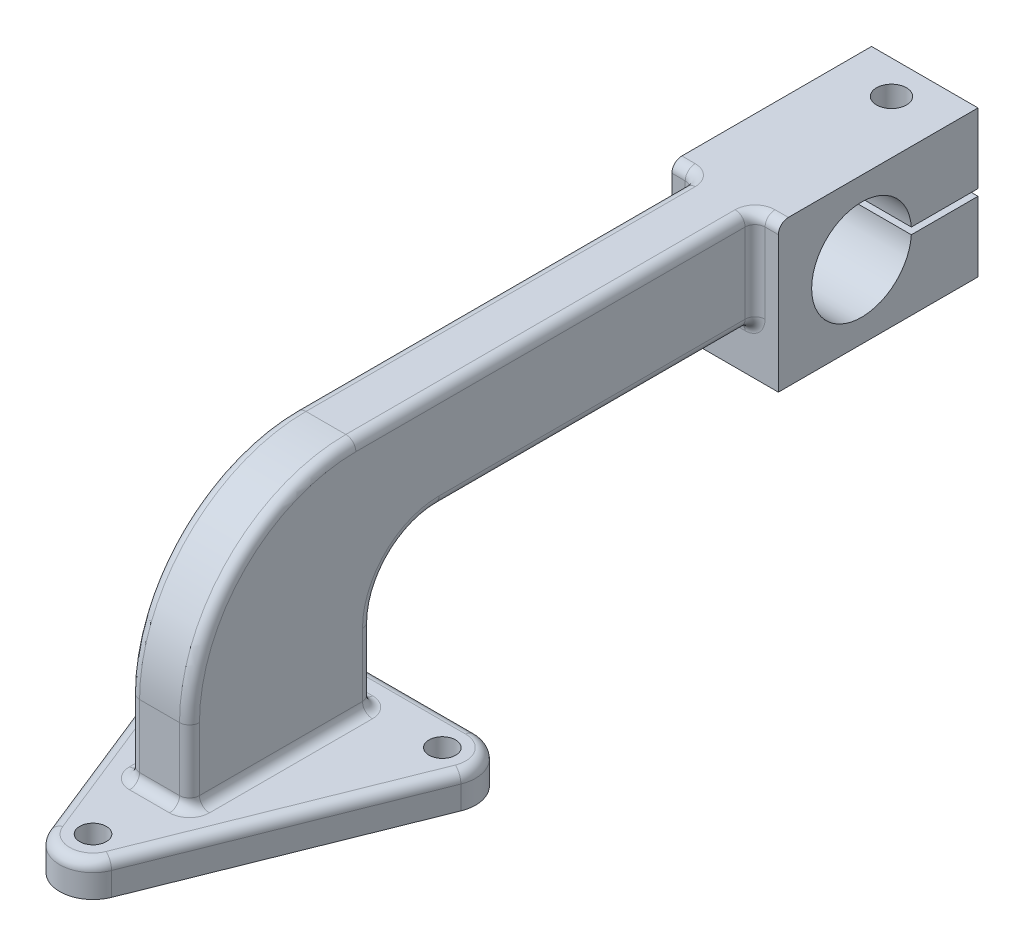
SolidWorks part; units mm, degrees
ref_plane "Front Plane" through (0, 0, 0) normal (0, 0, 1) x (1, 0, 0)
ref_plane "Top Plane" through (0, 0, 0) normal (0, 1, 0) x (1, 0, 0)
ref_plane "Right Plane" through (0, 0, 0) normal (1, 0, 0) x (0, 0, -1)
sketch "Sketch1" plane through (0, 0, 0) normal (1, 0, 0) x (0, 0, -1)
  line L0 (90.4912, -6.4386) -> (-4.5088, -6.4386)
  line L1 (-24.5088, -26.4386) -> (-24.5088, -48.4386)
  line L2 (-24.5088, -48.4386) -> (-79.5088, -48.4386)
  line L3 (-79.5088, -48.4386) -> (-79.5088, -37.4386)
  line L4 (-79.5088, -37.4386) -> (-79.5088, -26.4386)
  line L5 (-29.5088, 23.5614) -> (90.4912, 23.5614)
  line L6 (90.4912, 23.5614) -> (90.4912, -6.4386)
  arc A0 (-4.5088, -6.4386) -> (-24.5088, -26.4386) centre (-4.5088, -26.4386) ccw
  arc A1 (-79.5088, -26.4386) -> (-29.5088, 23.5614) centre (-29.5088, -26.4386) cw
  point P10 (0, 0)
  dimension "D4" = 20
  dimension "D5" = 50
  dimension "D1" = 22
  dimension "D2" = 22
  dimension "D3" = 55
  dimension "D6" = 95
  dimension "D7" = 30
extrude "Boss-Extrude1" add sketch "Sketch1" along normal mid plane 18
sketch "Sketch2" plane through (0, 0, -90.4912) normal (0, 0, -1) x (-1, 0, 0)
  line L0 (-16, 23.5614) -> (16, 23.5614)
  line L1 (16, 23.5614) -> (16, -20.4386)
  line L2 (16, -20.4386) -> (-16, -20.4386)
  line L3 (-16, -20.4386) -> (-16, 23.5614)
  line L4 (0, 23.5614) -> (0, -20.4386) construction
  line L5 (0, 23.5614) -> (0, -6.4386) construction
  line L6 (-9, 23.5614) -> (9, 23.5614) construction
  line L7 (-9, -6.4386) -> (9, -6.4386) construction
  line L8 (-16, 1.5614) -> (16, 1.5614) construction
  line L9 (-9, 8.5614) -> (9, 8.5614) construction
  line L10 (-9, -6.4386) -> (-9, 23.5614) construction
  line L11 (9, -6.4386) -> (9, 23.5614) construction
  point P20 (0, 0)
  dimension "D1" = 32
  dimension "D2" = 44
extrude "Boss-Extrude2" add sketch "Sketch2" along normal blind 60
sketch "Sketch3" plane through (16, 0, 0) normal (1, 0, 0) x (0, 0, -1)
  line L0 (150.4912, 23.5614) -> (150.4912, -20.4386) construction
  line L1 (150.4912, -20.4386) -> (90.4912, -20.4386) construction
  circle A0 centre (115.4912, 1.5614) radius 15
  dimension "D2" = 30
  dimension "D1" = 35
  dimension "D3" = 22
extrude "Cut-Extrude1" cut sketch "Sketch3" against normal blind 60
sketch "Sketch4" plane through (16, 0, 0) normal (1, 0, 0) x (0, 0, -1)
  line L0 (150.4912, 23.5614) -> (150.4912, -20.4386) construction
  line L1 (126.4881, 2.5614) -> (160.867, 2.5614)
  line L2 (126.4881, 2.5614) -> (126.4881, 0.5614)
  line L3 (126.4881, 0.5614) -> (160.867, 0.5614)
  line L4 (160.867, 2.5614) -> (160.867, 0.5614)
  point P4 (160.867, 1.5614)
  point P7 (150.4912, 1.5614)
  dimension "D1" = 2
extrude "Cut-Extrude2" cut sketch "Sketch4" against normal through all
sketch "Sketch5" plane through (0, 23.5614, 0) normal (0, 1, 0) x (1, 0, 0)
  line L0 (-16, 150.4912) -> (16, 150.4912) construction
  circle A0 centre (0, 140.4912) radius 4.5
  dimension "D2" = 9
  dimension "D1" = 16
  dimension "D3" = 10
extrude "Cut-Extrude3" cut sketch "Sketch5" against normal through all
sketch "Sketch6" plane through (0, -48.4386, 0) normal (0, -1, 0) x (1, 0, 0)
  line L0 (-30, 14.5088) -> (30, 14.5088)
  line L1 (39.2848, 28.2227) -> (9.2848, 103.2227)
  line L2 (-9.2848, 103.2227) -> (-39.2848, 28.2227)
  line L3 (0, 126.4346) -> (0, 14.5088) construction
  line L4 (-9, 52.0088) -> (9, 52.0088) construction
  line L5 (-9, 79.5088) -> (-9, 24.5088) construction
  line L6 (9, 79.5088) -> (9, 24.5088) construction
  line L7 (9, 79.5088) -> (-9, 79.5088) construction
  line L9 (9, 24.5088) -> (-9, 24.5088) construction
  arc A0 (-30, 14.5088) -> (-39.2848, 28.2227) centre (-30, 24.5088) cw
  arc A1 (9.2848, 103.2227) -> (-9.2848, 103.2227) centre (0, 99.5088) ccw
  arc A2 (30, 14.5088) -> (39.2848, 28.2227) centre (30, 24.5088) ccw
  circle A3 centre (30, 24.5088) radius 4
  circle A4 centre (-30, 24.5088) radius 4
  circle A5 centre (0, 99.5088) radius 4
  point P23 (0, 24.5088)
  dimension "D1" = 10
  dimension "D5" = 8
  dimension "D2" = 75
  dimension "D3" = 20
  dimension "D4" = 30
extrude "Boss-Extrude3" add sketch "Sketch6" along normal blind 10
fillet "Fillet1" radius 3 27 edges at (12.5, 23.5614, -90.4912) (-12.5, 23.5614, -90.4912) (38.2807, -48.4386, 18.9025) (0, -48.4386, 14.5088) (-38.2807, -48.4386, 18.9025) (-24.2848, -48.4386, 65.7227) (0, -48.4386, 109.5088) (9, -37.4386, 79.5088) (9, 8.9167, 64.8641) (-9, -37.4386, 79.5088) (-9, 8.9167, 64.8641) (-9, -37.4386, 24.5088) (-9, -12.2965, 18.6509) (9, -37.4386, 24.5088) (9, -12.2965, 18.6509) (24.2848, -48.4386, 65.7227) (9, 23.5614, -30.4912) (-9, 23.5614, -30.4912) (-9, -6.4386, -42.9912) (9, -6.4386, -42.9912) (9, 8.5614, -90.4912) (0, -6.4386, -90.4912) (-9, 8.5614, -90.4912) (9, -48.4386, 52.0088) (0, -48.4386, 24.5088) (0, -48.4386, 79.5088) (-9, -48.4386, 52.0088)
